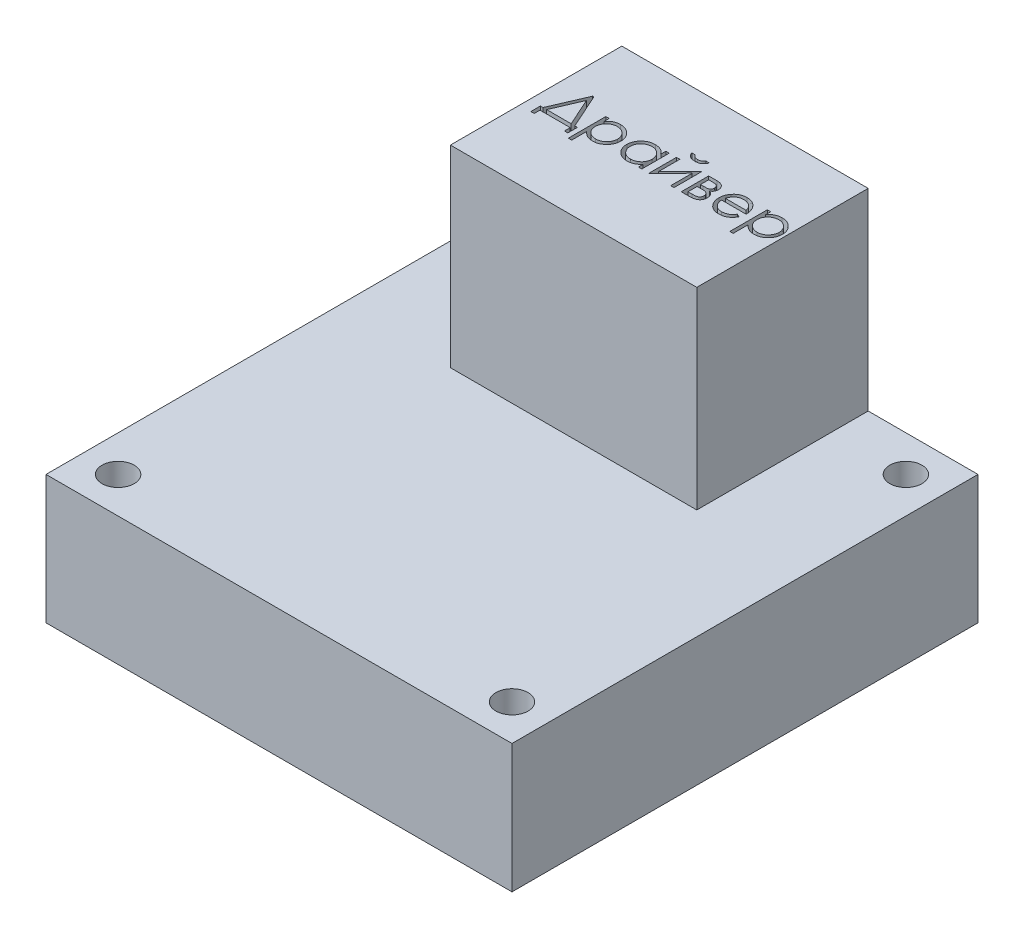
SolidWorks part; units mm, degrees
material "Кованное литое железо"
ref_plane "Спереди" through (0, 0, 0) normal (0, 0, 1) x (1, 0, 0)
ref_plane "Сверху" through (0, 0, 0) normal (0, 1, 0) x (1, 0, 0)
ref_plane "Справа" through (0, 0, 0) normal (1, 0, 0) x (0, 0, -1)
sketch "Эскиз1" plane through (0, 0, 0) normal (0, 1, 0) x (1, 0, 0)
  line L0 (0, 0) -> (18.3848, 18.3848) construction
  line L1 (-21.75, -21.75) -> (21.75, -21.75)
  line L2 (-21.75, -21.75) -> (-21.75, 21.75)
  line L3 (-21.75, 21.75) -> (21.75, 21.75)
  line L4 (21.75, -21.75) -> (21.75, 21.75)
  line L5 (-21.75, -21.75) -> (21.75, 21.75) construction
  line L6 (-21.75, 21.75) -> (21.75, -21.75) construction
  line L7 (-21.75, 0) -> (21.75, 0) construction
  line L8 (-18.3848, -18.3848) -> (18.3848, -18.3848) construction
  line L9 (-18.3848, -18.3848) -> (-18.3848, 18.3848) construction
  line L10 (-18.3848, 18.3848) -> (18.3848, 18.3848) construction
  line L11 (18.3848, -18.3848) -> (18.3848, 18.3848) construction
  line L12 (-18.3848, -18.3848) -> (18.3848, 18.3848) construction
  line L13 (-18.3848, 18.3848) -> (18.3848, -18.3848) construction
  circle A0 centre (-18.3848, 18.3848) radius 1.5
  circle A1 centre (18.3848, -18.3848) radius 1.5
  circle A2 centre (18.3848, 18.3848) radius 1.5
  circle A3 centre (-18.3848, -18.3848) radius 1.5
  point P0 (0, 0)
  dimension "D3" = 3
  dimension "D1" = 43.5
  dimension "D2" = 26
extrude "Бобышка-Вытянуть1" add sketch "Эскиз1" along normal blind 12
sketch "Эскиз2" plane through (0, 12, 0) normal (0, 1, 0) x (1, 0, 0)
  line L0 (0, 21.75) -> (0, -21.75) construction
  line L1 (21.75, 21.75) -> (-21.75, 21.75) construction
  line L2 (-21.75, -21.75) -> (21.75, -21.75) construction
  line L3 (0, 21.75) -> (0, 5.75) construction
  line L4 (0, 5.75) -> (-11.5, 5.75)
  line L5 (-11.5, 5.75) -> (-11.5, 21.75)
  line L6 (-11.5, 21.75) -> (11.5, 21.75)
  line L7 (11.5, 21.75) -> (11.5, 5.75)
  line L8 (11.5, 5.75) -> (0, 5.75)
  dimension "D1" = 16
  dimension "D2" = 11.5
  dimension "D3" = 11.5
extrude "Бобышка-Вытянуть2" add sketch "Эскиз2" along normal blind 18
sketch "Эскиз3" plane through (0, 30, 0) normal (0, 1, 0) x (1, 0, 0)
  text T0 "Драйвер\r\n"
extrude "Вырез-Вытянуть2" cut sketch "Эскиз3" against normal blind 2
